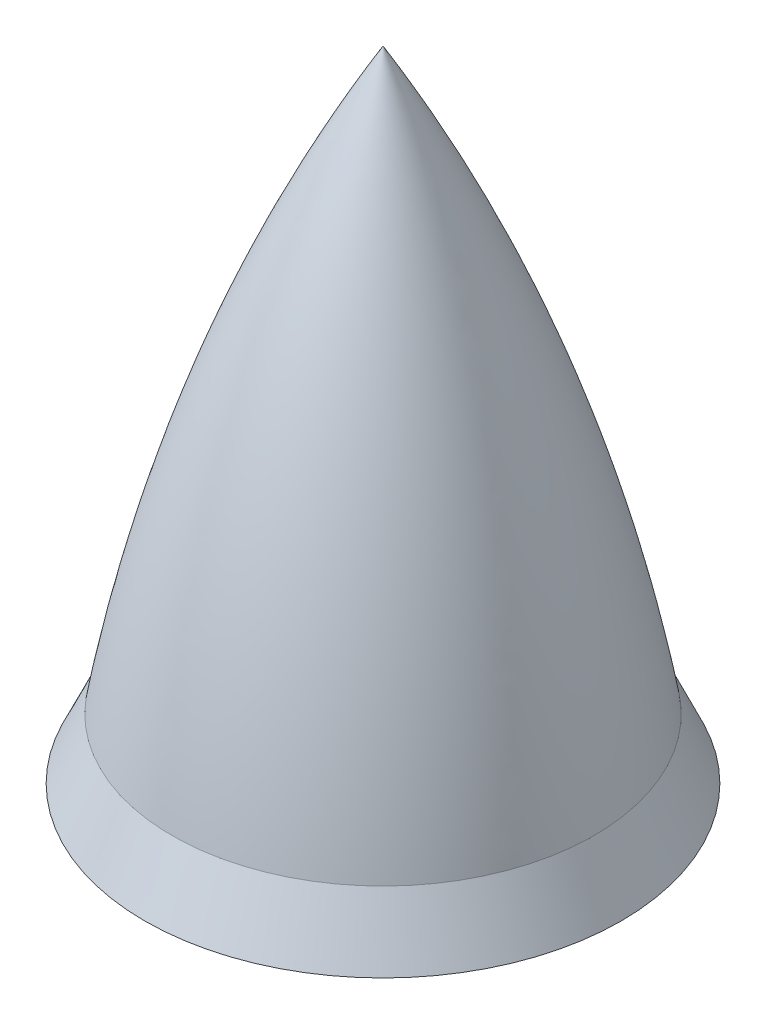
SolidWorks part; units mm, degrees
ref_plane "Front Plane" through (0, 0, 0) normal (0, 0, 1) x (1, 0, 0)
ref_plane "Top Plane" through (0, 0, 0) normal (0, 1, 0) x (1, 0, 0)
ref_plane "Right Plane" through (0, 0, 0) normal (1, 0, 0) x (0, 0, -1)
sketch "Sketch1" plane through (0, 0, 0) normal (0, 0, 1) x (1, 0, 0)
  line L0 (0, 0) -> (-5.93, 0)
  line L1 (0, 0) -> (0, 1.5)
  line L3 (-5.93, 0) -> (-5.25, 1.5)
  line L4 (0, 1.5) -> (0, 15.9)
  arc A0 (-5.25, 1.5) -> (0, 15.9) centre (37.5779, -5.9573) cw
  dimension "D1" = 5.93
  dimension "D2" = 1.5
  dimension "D3" = 5.25
  dimension "D4" = 14.4
revolve "Revolve2" add sketch "Sketch1" angle 360 about L4
sketch "Sketch2" plane through (0, 0, 0) normal (0, -1, 0) x (1, 0, 0)
  circle A0 centre (0, 0) radius 2.5
  dimension "D1" = 5
extrude "Cut-Extrude1" cut sketch "Sketch2" against normal blind 5
